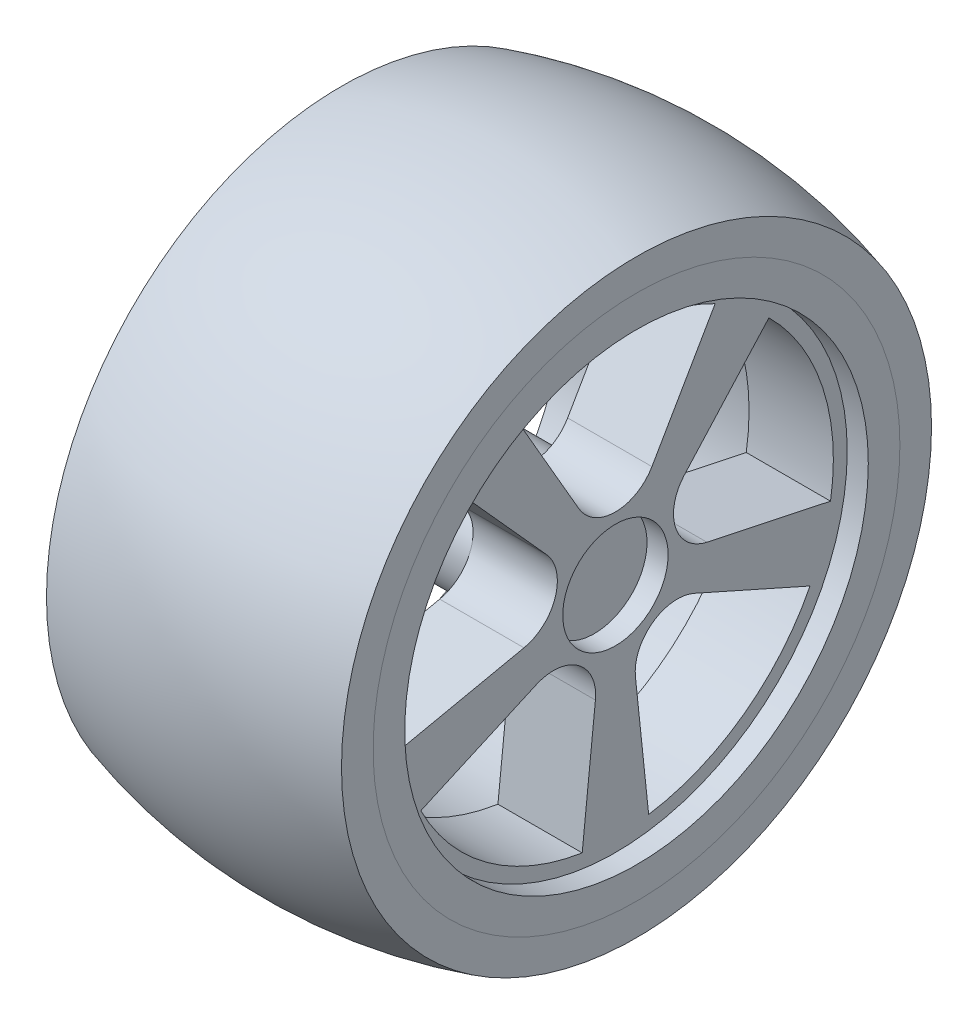
SolidWorks part; units mm, degrees
ref_plane "Front Plane" through (0, 0, 0) normal (0, 0, 1) x (1, 0, 0)
ref_plane "Top Plane" through (0, 0, 0) normal (0, 1, 0) x (1, 0, 0)
ref_plane "Right Plane" through (0, 0, 0) normal (1, 0, 0) x (0, 0, -1)
sketch "Sketch1" plane through (0, 0, 0) normal (0, 0, 1) x (1, 0, 0)
  line L0 (0, 0) -> (-33, 0)
  line L1 (-33, 0) -> (-33, 6)
  line L2 (-33, 6) -> (-10, 6)
  line L3 (-10, 6) -> (-10, 21)
  line L4 (-10, 21) -> (-28, 21)
  line L5 (-28, 21) -> (-28, 25)
  line L6 (-28, 25) -> (-26, 25)
  line L7 (-26, 25) -> (-26, 23)
  line L8 (-26, 23) -> (-2, 23)
  line L9 (-2, 23) -> (-2, 25)
  line L10 (-2, 25) -> (0, 25)
  line L11 (0, -55) -> (0, 55) construction
  line L12 (0, 0) -> (0, 25)
  dimension "D1" = 33
  dimension "D2" = 10
  dimension "D3" = 6
  dimension "D4" = 28
  dimension "D5" = 0
  dimension "D6" = 2
  dimension "D7" = 2
  dimension "D8" = 2
  dimension "D9" = 2
  dimension "D10" = 2
  dimension "D11" = 25
revolve "Revolve1" add sketch "Sketch1" angle 360 about L0
sketch "Sketch3" plane through (0, 0, 0) normal (1, 0, 0) x (0, 0, -1)
  circle A0 centre (0, 0) radius 22
  circle A1 centre (0, 0) radius 25 construction
  dimension "D1" = 3
extrude "Cut-Extrude1" cut sketch "Sketch3" against normal blind 2
sketch "Sketch2" plane through (-2, 0, 0) normal (1, 0, 0) x (0, 0, -1)
  line L0 (0, 18.15) -> (0, -18.15) construction
  line L1 (-9.4642, 18.3923) -> (-3.4642, 8)
  line L2 (9.4642, 18.3923) -> (3.4642, 8)
  line L3 (20.4167, -3.3174) -> (8.679, -0.8225)
  line L4 (14.5676, 14.6845) -> (6.538, 5.7668)
  line L5 (3.1541, -20.4426) -> (1.8997, -8.5083)
  line L6 (18.4674, -9.3168) -> (7.5049, -4.436)
  line L7 (-18.4674, -9.3168) -> (-7.5049, -4.436)
  line L8 (-3.1541, -20.4426) -> (-1.8997, -8.5083)
  line L9 (-14.5676, 14.6845) -> (-6.538, 5.7668)
  line L10 (-20.4167, -3.3174) -> (-8.679, -0.8225)
  arc A0 (-3.4642, 8) -> (3.4642, 8) centre (0, 10.0001) ccw
  arc A1 (-9.4642, 18.3923) -> (9.4642, 18.3923) centre (0, 0) cw
  arc A3 (6.538, 5.7668) -> (8.679, -0.8225) centre (9.5106, 3.0902) ccw
  arc A4 (14.5676, 14.6845) -> (20.4167, -3.3174) centre (0, 0) cw
  arc A5 (7.5049, -4.436) -> (1.8997, -8.5083) centre (5.8779, -8.0902) ccw
  arc A6 (18.4674, -9.3168) -> (3.1541, -20.4426) centre (0, 0) cw
  arc A7 (-1.8997, -8.5083) -> (-7.5049, -4.436) centre (-5.8779, -8.0902) ccw
  arc A8 (-3.1541, -20.4426) -> (-18.4674, -9.3168) centre (0, 0) cw
  arc A9 (-8.679, -0.8225) -> (-6.538, 5.7668) centre (-9.5106, 3.0902) ccw
  arc A10 (-20.4167, -3.3174) -> (-14.5676, 14.6845) centre (0, 0) cw
  point P1 (0, 6)
  dimension "D1" = 6
  dimension "D3" = 5
  dimension "D4" = 4.0001
  dimension "D2" = 60
  dimension "D5" = 12
extrude "Cut-Extrude2" cut sketch "Sketch2" against normal through all
sketch "Sketch4" plane through (-2, 0, 0) normal (1, 0, 0) x (0, 0, -1)
  circle A0 centre (0, 0) radius 5
extrude "Cut-Extrude3" cut sketch "Sketch4" against normal blind 2
sketch "Sketch5" plane through (-33, 0, 0) normal (-1, 0, 0) x (0, 0, 1)
  line L0 (-2.5981, 1.5) -> (2.5981, 1.5)
  line L2 (2.5981, -1.5) -> (-2.5981, -1.5)
  arc A0 (-2.5981, 1.5) -> (-2.5981, -1.5) centre (0, 0) ccw
  arc A1 (2.5981, -1.5) -> (2.5981, 1.5) centre (0, 0) ccw
  dimension "D1" = 3
  dimension "D2" = 1.5
extrude "Cut-Extrude4" cut sketch "Sketch5" against normal blind 7
sketch "Sketch7" plane through (0, 0, 0) normal (0, 0, 1) x (1, 0, 0)
  line L0 (-14, -23) -> (-14, -2.2638) construction
  line L1 (-26, -23) -> (-2, -23) construction
  line L2 (-14, 26) -> (-24, 26)
  line L3 (-24, 26) -> (-24, 23)
  line L4 (-24, 23) -> (-26, 23)
  line L5 (-26, 23) -> (-26, 25)
  line L6 (-26, 25) -> (-28, 25)
  line L7 (-28, 25) -> (-28, 28)
  line L8 (18.15, 0) -> (-18.15, 0) construction
  line L9 (-14, 26) -> (-4, 26)
  line L10 (-4, 26) -> (-4, 23)
  line L11 (-4, 23) -> (-2, 23)
  line L12 (-2, 23) -> (-2, 25)
  line L13 (-2, 25) -> (0, 25)
  line L14 (0, 25) -> (0, 28)
  line L15 (0, 0) -> (-8.6261, 0) construction
  arc A0 (-28, 28) -> (0, 28) centre (-14, -20) cw
  point P13 (-19, 26)
  point P14 (-26, 24)
  dimension "D1" = 25
  dimension "D2" = 14
  dimension "D3" = 3
  dimension "D4" = 2
  dimension "D5" = 2
  dimension "D6" = 2
  dimension "D8" = 3
revolve "Revolve3" add sketch "Sketch7" angle 360 about L15
